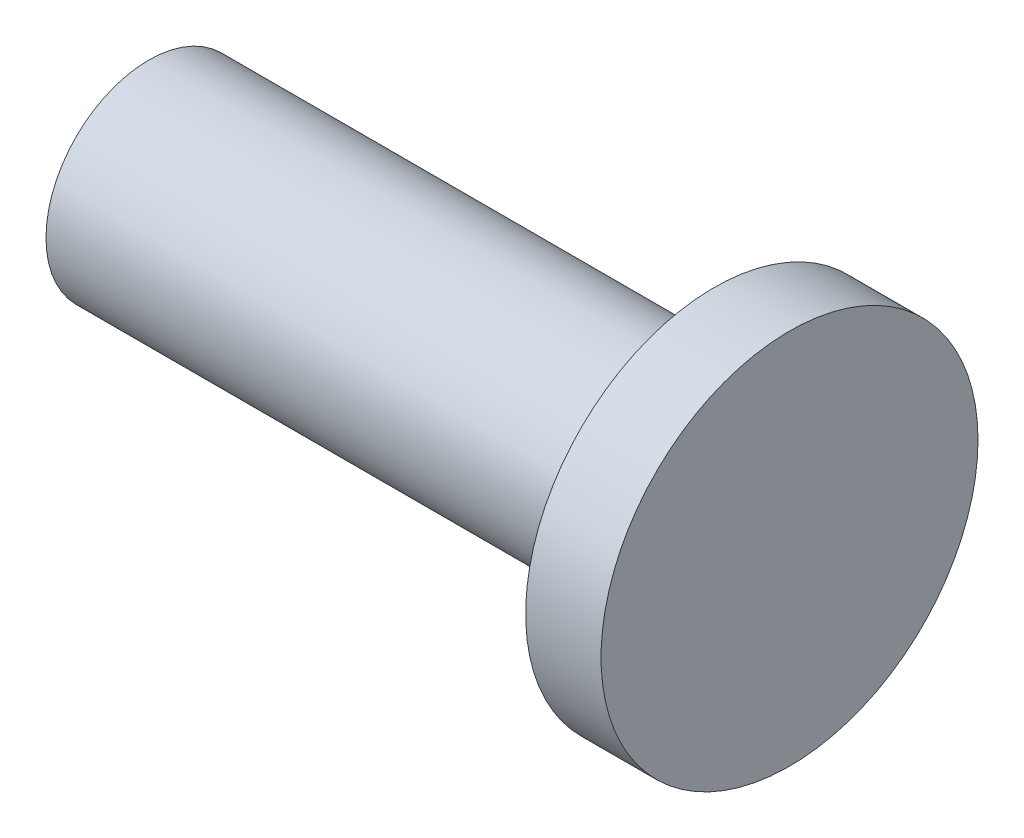
SolidWorks part; units mm, degrees
ref_plane "Front Plane" through (0, 0, 0) normal (0, 0, 1) x (1, 0, 0)
ref_plane "Top Plane" through (0, 0, 0) normal (0, 1, 0) x (1, 0, 0)
ref_plane "Right Plane" through (0, 0, 0) normal (1, 0, 0) x (0, 0, -1)
sketch "Sketch1" plane through (0, 0, 0) normal (1, 0, 0) x (0, 0, -1)
  circle A0 centre (0, 0) radius 2.725
  dimension "D1" = 5.45
extrude "Boss-Extrude1" add sketch "Sketch1" along normal blind 15
sketch "Sketch2" plane through (15, 0, 0) normal (1, 0, 0) x (0, 0, -1)
  circle A0 centre (0, 0) radius 5
  dimension "D1" = 10
extrude "Boss-Extrude2" add sketch "Sketch2" along normal blind 2
